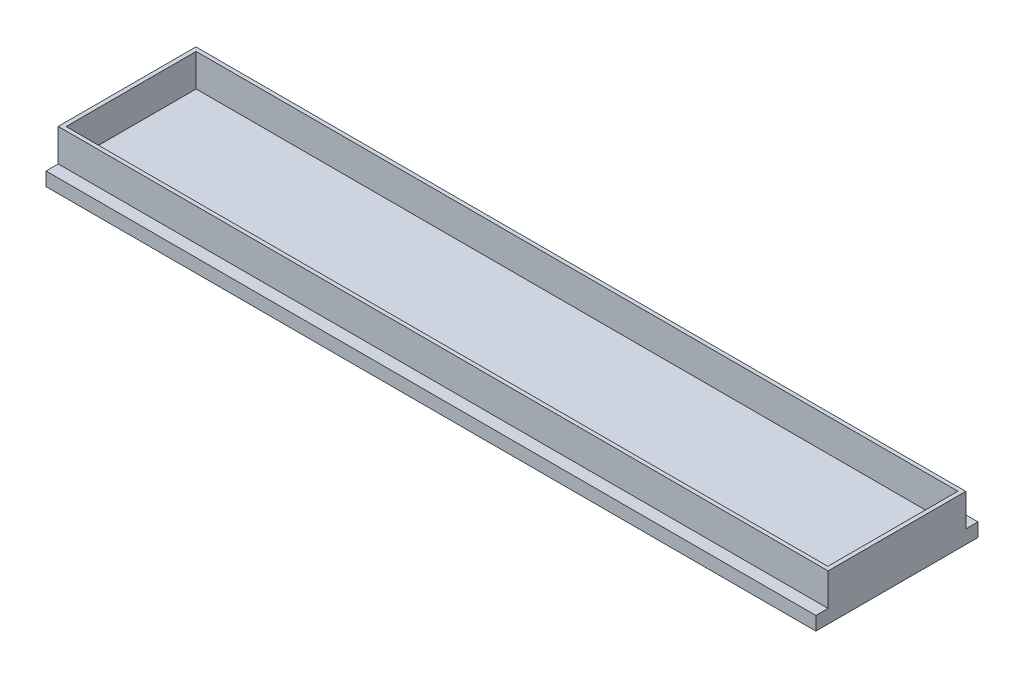
SolidWorks part; units mm, degrees
ref_plane "Front Plane" through (0, 0, 0) normal (0, 0, 1) x (1, 0, 0)
ref_plane "Top Plane" through (0, 0, 0) normal (0, 1, 0) x (1, 0, 0)
ref_plane "Right Plane" through (0, 0, 0) normal (1, 0, 0) x (0, 0, -1)
sketch "Sketch2" plane through (0, 0, 0) normal (0, 1, 0) x (1, 0, 0)
  line L0 (710, 149.5) -> (-710, 149.5)
  line L6 (-710, 149.5) -> (-710, -149.5)
  line L7 (710, -149.5) -> (-710, -149.5)
  line L8 (710, 149.5) -> (710, -149.5)
  point P0 (0, 0)
extrude "Boss-Extrude1" add sketch "Sketch2" along normal blind 25
sketch "Sketch3" plane through (0, 25, 0) normal (0, 1, 0) x (1, 0, 0)
  line L0 (710, 127) -> (-710, 127)
  line L6 (-710, 127) -> (-710, -127)
  line L10 (-702.5, -120) -> (-702.5, 120)
  line L11 (710, 127) -> (710, -127)
  line L12 (702.5, -120) -> (702.5, 120)
  line L13 (710, -127) -> (-710, -127)
  line L14 (702.5, -120) -> (-702.5, -120)
  line L15 (702.5, 120) -> (-702.5, 120)
  point P0 (0, 0)
  point P7 (0, 0)
extrude "Boss-Extrude2" add sketch "Sketch3" along normal blind 60
sketch "Sketch4" plane through (0, 0, 0) normal (0, -1, 0) x (1, 0, 0)
  line L0 (710, 0) -> (-710, 0)
  line L2 (0, 149.5) -> (0, -149.5)
  line L4 (-710, 149.5) -> (710, 149.5) construction
  line L5 (710, -149.5) -> (-710, -149.5) construction
